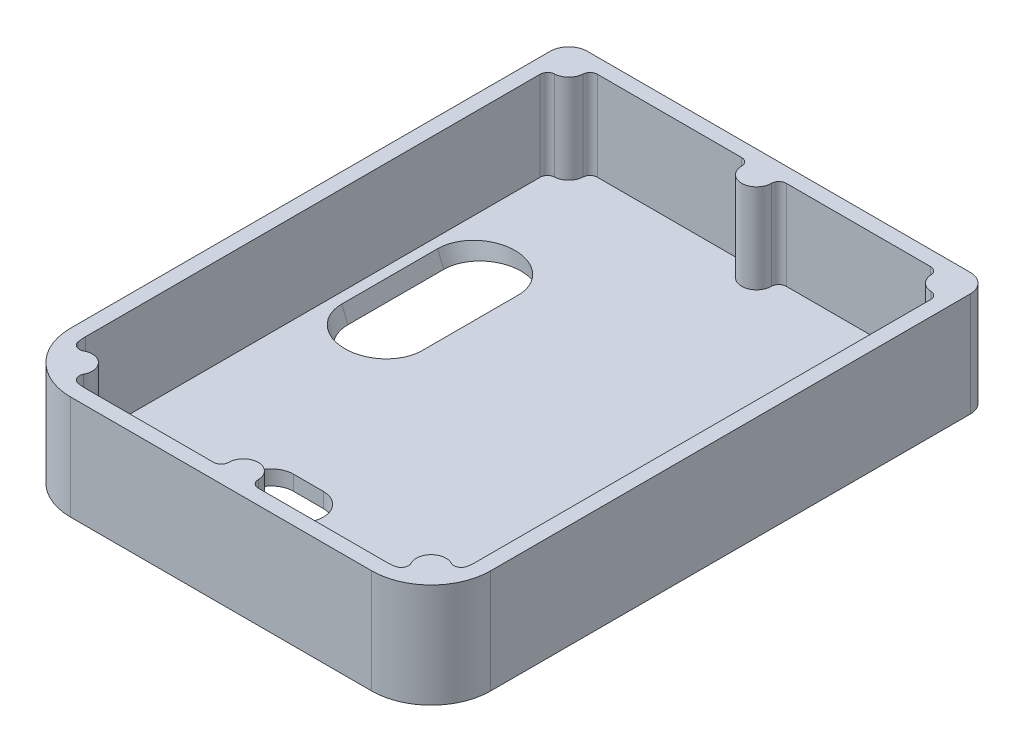
SolidWorks part; units mm, degrees
ref_plane "Front Plane" through (0, 0, 0) normal (0, 0, 1) x (1, 0, 0)
ref_plane "Top Plane" through (0, 0, 0) normal (0, 1, 0) x (1, 0, 0)
ref_plane "Right Plane" through (0, 0, 0) normal (1, 0, 0) x (0, 0, -1)
sketch "Sketch1" plane through (0, 0, 0) normal (0, 1, 0) x (1, 0, 0)
  line L1 (-81.7562, 119.0625) -> (81.7562, 119.0625)
  line L2 (-89.6938, 111.125) -> (-89.6937, -93.6625)
  line L3 (-64.2937, -119.0625) -> (64.2937, -119.0625)
  line L4 (89.6938, 111.125) -> (89.6938, -93.6625)
  line L5 (-89.6938, 119.0625) -> (89.6938, -119.0625) construction
  line L6 (-89.6937, -119.0625) -> (89.6938, 119.0625) construction
  arc A0 (64.2937, -119.0625) -> (89.6938, -93.6625) centre (64.2938, -93.6625) ccw
  arc A1 (-89.6937, -93.6625) -> (-64.2937, -119.0625) centre (-64.2937, -93.6625) ccw
  arc A2 (81.7562, 119.0625) -> (89.6938, 111.125) centre (81.7563, 111.125) cw
  arc A3 (-81.7562, 119.0625) -> (-89.6938, 111.125) centre (-81.7563, 111.125) ccw
  point P0 (0, 0)
  dimension "D3" = 25.4
  dimension "D4" = 7.9375
  dimension "D1" = 238.125
  dimension "D2" = 179.3875
extrude "Boss-Extrude1" add sketch "Sketch1" along normal blind 6.35
sketch "Sketch2" plane through (0, 6.35, 0) normal (0, 1, 0) x (1, 0, 0)
  line L0 (81.7562, 112.7125) -> (-81.7562, 112.7125)
  line L1 (-83.3438, 111.125) -> (-83.3438, -93.6625)
  line L2 (-64.2937, -112.7125) -> (64.2937, -112.7125)
  line L3 (83.3438, -93.6625) -> (83.3438, 111.125)
  line L4 (89.6938, -93.6625) -> (89.6938, 111.125)
  line L5 (81.7562, 119.0625) -> (-81.7562, 119.0625)
  line L6 (-89.6938, 111.125) -> (-89.6937, -93.6625)
  line L7 (-64.2937, -119.0625) -> (64.2937, -119.0625)
  line L8 (89.6938, -93.6625) -> (89.6938, 111.125)
  line L9 (81.7562, 119.0625) -> (-81.7562, 119.0625)
  line L10 (-89.6938, 111.125) -> (-89.6937, -93.6625)
  line L11 (-64.2937, -119.0625) -> (64.2937, -119.0625)
  arc A0 (-81.7562, 112.7125) -> (-83.3438, 111.125) centre (-81.7563, 111.125) ccw
  arc A1 (-83.3438, -93.6625) -> (-64.2937, -112.7125) centre (-64.2937, -93.6625) ccw
  arc A2 (64.2937, -112.7125) -> (83.3438, -93.6625) centre (64.2938, -93.6625) ccw
  arc A3 (83.3438, 111.125) -> (81.7562, 112.7125) centre (81.7563, 111.125) ccw
  arc A4 (64.2937, -119.0625) -> (89.6938, -93.6625) centre (64.2938, -93.6625) ccw
  arc A5 (89.6938, 111.125) -> (81.7562, 119.0625) centre (81.7563, 111.125) ccw
  arc A6 (-81.7562, 119.0625) -> (-89.6938, 111.125) centre (-81.7563, 111.125) ccw
  arc A7 (-89.6937, -93.6625) -> (-64.2937, -119.0625) centre (-64.2937, -93.6625) ccw
  arc A8 (64.2937, -119.0625) -> (89.6938, -93.6625) centre (64.2938, -93.6625) ccw
  arc A9 (89.6938, 111.125) -> (81.7562, 119.0625) centre (81.7563, 111.125) ccw
  arc A10 (-81.7562, 119.0625) -> (-89.6938, 111.125) centre (-81.7563, 111.125) ccw
  arc A11 (-89.6937, -93.6625) -> (-64.2937, -119.0625) centre (-64.2937, -93.6625) ccw
  dimension "D1" = 0
  dimension "D2" = 6.35
extrude "Boss-Extrude2" add sketch "Sketch2" along normal blind 38.1
ref_plane "Plane1" through (-13.1353, 31.7115, 0) normal (-0.3827, 0.9239, 0) x (0, 0, 1)
sketch "Sketch5" plane through (-13.1353, 31.7115, 0) normal (-0.3827, 0.9239, 0) x (0, 0, 1)
  line L0 (-52.2137, -70.395) -> (-11.2863, -70.395) construction
  line L1 (-11.2863, -38.645) -> (-52.2137, -38.645) construction
  line L2 (-52.2137, -70.395) -> (-11.2863, -70.395)
  line L3 (-11.2863, -38.645) -> (-52.2137, -38.645)
  spline S0 degree 3 poles (-11.2863, -70.395) (20.4637, -70.395) (20.4637, -38.645) (-11.2863, -38.645) knots 0 0 0 0 1 1 1 1 weights 1 0.333333 0.333333 1 construction
  spline S1 degree 3 poles (-11.2863, -70.395) (20.4637, -70.395) (20.4637, -38.645) (-11.2863, -38.645) knots 0 0 0 0 1 1 1 1 weights 1 0.333333 0.333333 1
  spline S2 degree 3 poles (-52.2137, -70.395) (-83.9637, -70.395) (-83.9637, -38.645) (-52.2137, -38.645) knots 0 0 0 0 1 1 1 1 weights 1 0.333333 0.333333 1 construction
  spline S3 degree 3 poles (-52.2137, -70.395) (-83.9637, -70.395) (-83.9637, -38.645) (-52.2137, -38.645) knots 0 0 0 0 1 1 1 1 weights 1 0.333333 0.333333 1
extrude "Cut-Extrude1" cut sketch "Sketch5" against normal blind 25.4 and the other way blind 12.7
ref_plane "Plane2" through (13.1353, 31.7115, 0) normal (0.3827, 0.9239, 0) x (0, 0, -1)
sketch "Sketch7" plane through (13.1353, 31.7115, 0) normal (0.3827, 0.9239, 0) x (0, 0, -1)
  line L0 (10.2044, -72.1467) -> (53.2955, -72.1467) construction
  line L1 (53.2955, -40.3967) -> (10.2044, -40.3967) construction
  line L2 (10.2044, -72.1467) -> (53.2955, -72.1467)
  line L3 (53.2955, -40.3967) -> (10.2044, -40.3967)
  spline S0 degree 3 poles (53.2955, -40.3967) (85.0455, -40.3967) (85.0455, -72.1467) (53.2955, -72.1467) knots 0 0 0 0 1 1 1 1 weights 1 0.333333 0.333333 1 construction
  spline S1 degree 3 poles (10.2044, -72.1467) (-21.5456, -72.1467) (-21.5456, -40.3967) (10.2044, -40.3967) knots 0 0 0 0 1 1 1 1 weights 1 0.333333 0.333333 1 construction
  spline S2 degree 3 poles (53.2955, -40.3967) (85.0455, -40.3967) (85.0455, -72.1467) (53.2955, -72.1467) knots 0 0 0 0 1 1 1 1 weights 1 0.333333 0.333333 1
  spline S3 degree 3 poles (10.2044, -72.1467) (-21.5456, -72.1467) (-21.5456, -40.3967) (10.2044, -40.3967) knots 0 0 0 0 1 1 1 1 weights 1 0.333333 0.333333 1
extrude "Cut-Extrude2" cut sketch "Sketch7" against normal blind 25.4 and the other way blind 6.35
sketch "Sketch8" plane through (0, 0, 0) normal (0, -1, 0) x (1, 0, 0)
  line L0 (13.4938, 97.3138) -> (26.1938, 97.3138) construction
  line L1 (13.4938, 106.8388) -> (26.1938, 106.8388)
  line L2 (13.4938, 87.7888) -> (26.1938, 87.7888)
  line L3 (89.6938, 93.6625) -> (89.6938, -111.125) construction
  line L4 (-64.2937, 119.0625) -> (64.2937, 119.0625) construction
  line L5 (-26.1937, 71.4375) -> (-13.4937, 71.4375) construction
  line L6 (-26.1937, 80.9625) -> (-13.4937, 80.9625)
  line L7 (-26.1937, 61.9125) -> (-13.4937, 61.9125)
  arc A0 (13.4938, 106.8388) -> (13.4938, 87.7888) centre (13.4938, 97.3138) ccw
  arc A1 (26.1938, 87.7888) -> (26.1938, 106.8388) centre (26.1938, 97.3138) ccw
  arc A2 (-26.1937, 80.9625) -> (-26.1937, 61.9125) centre (-26.1937, 71.4375) ccw
  arc A3 (-13.4937, 61.9125) -> (-13.4937, 80.9625) centre (-13.4937, 71.4375) ccw
  point P2 (19.8438, 97.3138)
  point P7 (-19.8437, 71.4375)
  dimension "D2" = 9.525
  dimension "D4" = 12.7
  dimension "D5" = 9.525
  dimension "D1" = 69.85
  dimension "D3" = 21.7487
  dimension "D6" = 47.625
  dimension "D7" = 12.7
  dimension "D8" = 109.5375
extrude "Cut-Extrude3" cut sketch "Sketch8" against normal through all
sketch "Sketch9" plane through (0, 6.35, 0) normal (0, 1, 0) x (1, 0, 0)
  line L0 (-87.3689, 116.7377) -> (-80.6337, 110.0025) construction
  line L1 (-64.2937, -112.7125) -> (64.2937, -112.7125) construction
  line L5 (-64.2937, -112.7125) -> (64.2937, -112.7125) construction
  line L6 (-81.7562, 112.7125) -> (-71.1201, 112.7125)
  line L10 (81.7562, 112.7125) -> (-81.7562, 112.7125) construction
  line L11 (-83.3438, 111.125) -> (-83.3438, 100.4888)
  line L12 (-83.3438, 111.125) -> (-83.3438, -93.6625) construction
  line L14 (-82.2543, -111.623) -> (-64.2937, -93.6625) construction
  line L15 (-9.525, -112.7125) -> (9.525, -112.7125)
  line L16 (-133.9237, 0) -> (138.4201, 0) construction
  line L17 (0, 128.5214) -> (0, -157.9151) construction
  line L18 (-9.525, 112.7125) -> (9.525, 112.7125)
  line L19 (83.3438, 111.125) -> (83.3438, 100.4888)
  line L20 (81.7562, 112.7125) -> (71.1201, 112.7125)
  arc A4 (-83.0494, -96.9983) -> (-78.4553, -99.2575) centre (-79.9235, -96.4423) ccw
  circle A5 centre (-80.6337, 110.0025) radius 3.175 construction
  arc A7 (-69.8887, -107.8241) -> (-67.6295, -112.4182) centre (-67.0735, -109.2922) ccw
  circle A10 centre (0, -109.5375) radius 3.175 construction
  arc A13 (6.35, -109.5375) -> (-6.35, -109.5375) centre (0, -109.5375) ccw
  arc A14 (-6.35, -109.5375) -> (-9.525, -112.7125) centre (-9.525, -109.5375) cw
  arc A15 (-81.7562, 112.7125) -> (-83.3438, 111.125) centre (-81.7563, 111.125) ccw construction
  arc A24 (-81.7562, 119.0625) -> (-89.6938, 111.125) centre (-81.7563, 111.125) ccw construction
  arc A25 (-81.7562, 119.0625) -> (-89.6938, 111.125) centre (-81.7563, 111.125) ccw construction
  arc A26 (-80.3237, 103.66) -> (-74.2913, 109.6925) centre (-80.6337, 110.0025) ccw
  arc A27 (-81.7562, 112.7125) -> (-83.3438, 111.125) centre (-81.7563, 111.125) ccw
  arc A28 (-80.3237, 103.66) -> (-83.3438, 100.4888) centre (-80.1687, 100.4888) ccw
  arc A29 (-74.2913, 109.6925) -> (-71.1201, 112.7125) centre (-71.1201, 109.5375) cw
  circle A30 centre (-75.5191, -104.8878) radius 3.175 construction
  arc A31 (-83.3438, -93.6625) -> (-64.2937, -112.7125) centre (-64.2937, -93.6625) ccw construction
  arc A32 (-89.6937, -93.6625) -> (-64.2937, -119.0625) centre (-64.2937, -93.6625) ccw construction
  arc A33 (-89.6937, -93.6625) -> (-64.2937, -119.0625) centre (-64.2937, -93.6625) ccw construction
  arc A34 (-69.8887, -107.8241) -> (-78.4553, -99.2575) centre (-75.5191, -104.8878) ccw
  arc A35 (-83.0494, -96.9983) -> (-67.6295, -112.4182) centre (-64.2937, -93.6625) ccw
  arc A36 (6.35, -109.5375) -> (9.525, -112.7125) centre (9.525, -109.5375) ccw
  arc A37 (-6.35, 109.5375) -> (-9.525, 112.7125) centre (-9.525, 109.5375) ccw
  arc A38 (6.35, 109.5375) -> (-6.35, 109.5375) centre (0, 109.5375) cw
  arc A39 (6.35, 109.5375) -> (9.525, 112.7125) centre (9.525, 109.5375) cw
  arc A40 (69.8887, -107.8241) -> (67.6295, -112.4182) centre (67.0735, -109.2922) cw
  arc A41 (83.0494, -96.9983) -> (67.6295, -112.4182) centre (64.2937, -93.6625) cw
  arc A42 (83.0494, -96.9983) -> (78.4553, -99.2575) centre (79.9235, -96.4423) cw
  arc A43 (69.8887, -107.8241) -> (78.4553, -99.2575) centre (75.5191, -104.8878) cw
  arc A44 (81.7562, 112.7125) -> (83.3438, 111.125) centre (81.7563, 111.125) cw
  arc A45 (80.3237, 103.66) -> (83.3438, 100.4888) centre (80.1687, 100.4888) cw
  arc A46 (80.3237, 103.66) -> (74.2913, 109.6925) centre (80.6337, 110.0025) cw
  arc A47 (74.2913, 109.6925) -> (71.1201, 112.7125) centre (71.1201, 109.5375) ccw
  point P43 (0, -112.7125)
  dimension "D1" = 6.35
  dimension "D2" = 12.7
  dimension "D3" = 3.175
  dimension "D4" = 6.35
  dimension "D5" = 12.7
  dimension "D6" = 3.175
  dimension "D7" = 6.35
  dimension "D8" = 12.7
  dimension "D9" = 3.175
extrude "Boss-Extrude3" add sketch "Sketch9" along normal up to surface (38.1 mm away) up to face at (0, 44.45, -3.4615)
